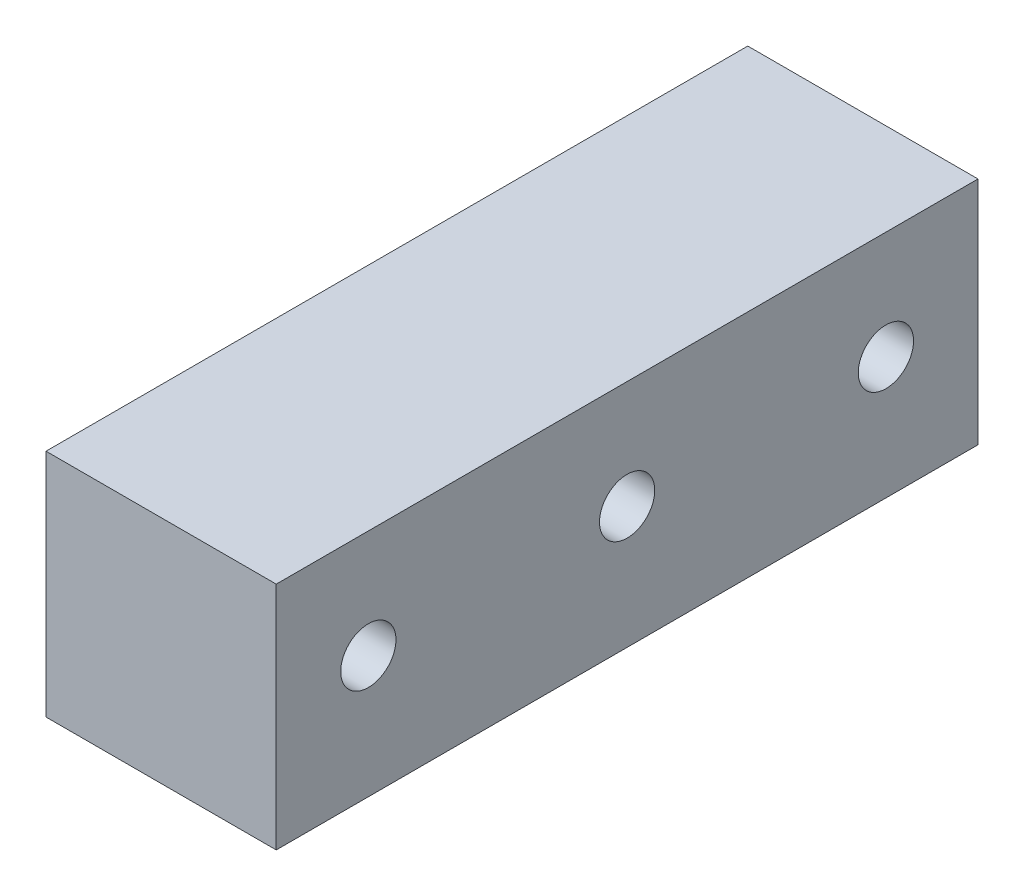
SolidWorks part; units mm, degrees
ref_plane "Front Plane" through (0, 0, 0) normal (0, 0, 1) x (1, 0, 0)
ref_plane "Top Plane" through (0, 0, 0) normal (0, 1, 0) x (1, 0, 0)
ref_plane "Right Plane" through (0, 0, 0) normal (1, 0, 0) x (0, 0, -1)
sketch "Sketch1" plane through (0, 0, 0) normal (0, 1, 0) x (1, 0, 0)
  line L1 (-25, 76.2) -> (25, 76.2)
  line L2 (-25, 76.2) -> (-25, -76.2)
  line L3 (-25, -76.2) -> (25, -76.2)
  line L4 (25, 76.2) -> (25, -76.2)
  line L5 (-25, 76.2) -> (25, -76.2) construction
  line L6 (-25, -76.2) -> (25, 76.2) construction
  point P0 (0, 0)
  dimension "D1" = 50
  dimension "D2" = 152.4
extrude "Boss-Extrude1" add sketch "Sketch1" along normal blind 50
sketch "Sketch2" plane through (25, 0, 0) normal (1, 0, 0) x (0, 0, -1)
  line L0 (-76.2, 50) -> (-76.2, 0) construction
  line L1 (76.2, 50) -> (76.2, 0) construction
  circle A0 centre (-56.2, 26.5505) radius 6
  circle A1 centre (0, 26.5505) radius 6
  circle A2 centre (56.2, 26.5505) radius 6
  point P6 (0, 0)
  point P7 (0, 0)
  point P8 (0, 0)
  dimension "D1" = 12
  dimension "D2" = 112.4
  dimension "D3" = 20
  dimension "D4" = 20
  dimension "D5" = 56.2
extrude "Cut-Extrude1" cut sketch "Sketch2" against normal through all
